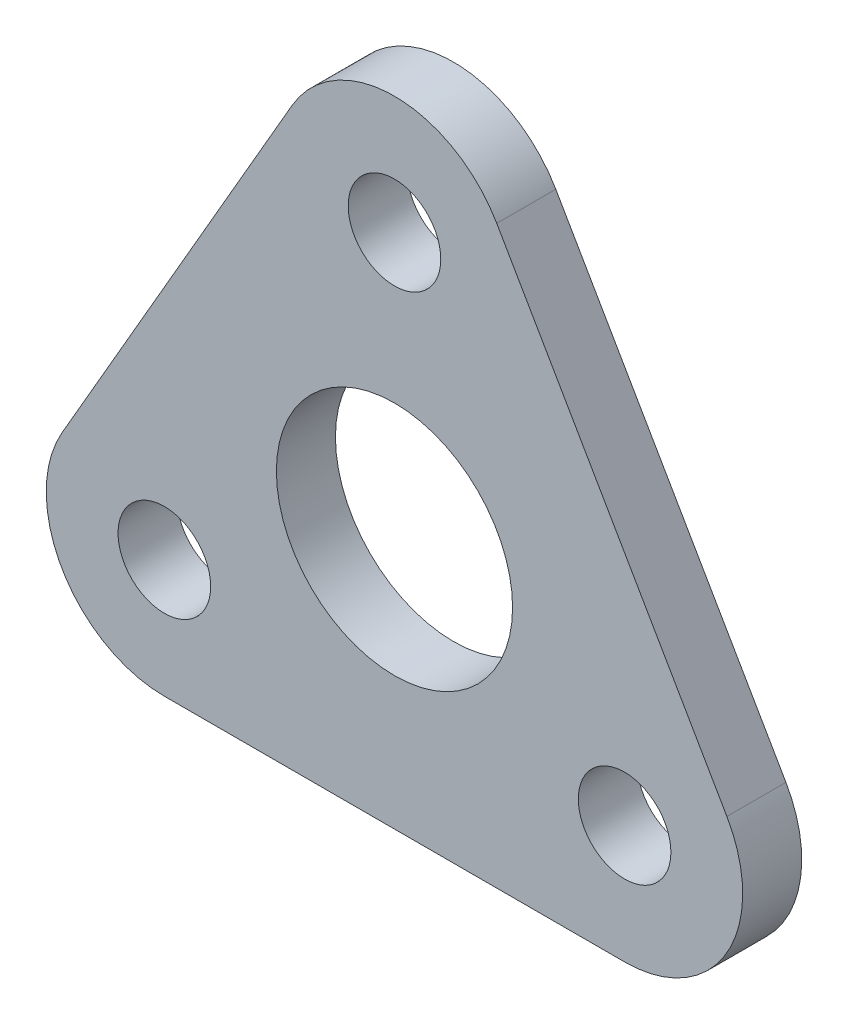
SolidWorks part; units mm, degrees
material "6061-T6 (SS)"
ref_plane "Front Plane" through (0, 0, 0) normal (0, 0, 1) x (1, 0, 0)
ref_plane "Top Plane" through (0, 0, 0) normal (0, 1, 0) x (1, 0, 0)
ref_plane "Right Plane" through (0, 0, 0) normal (1, 0, 0) x (0, 0, -1)
sketch "Sketch1" plane through (0, 0, 0) normal (0, 0, 1) x (1, 0, 0)
  line L3 (0, 14.2875) -> (12.3733, -7.1438) construction
  line L4 (12.3733, -7.1438) -> (-12.3733, -7.1438) construction
  line L5 (-12.3733, -7.1438) -> (0, 14.2875) construction
  line L6 (0, 26.9875) -> (23.3719, -13.4938)
  line L7 (23.3719, -13.4938) -> (-23.3719, -13.4938)
  line L8 (-23.3719, -13.4938) -> (0, 26.9875)
  circle A0 centre (0, 0) radius 6.35
  circle A1 centre (0, 14.2875) radius 2.4892
  circle A2 centre (12.3733, -7.1438) radius 2.4892
  circle A3 centre (-12.3733, -7.1438) radius 2.4892
  point P11 (0, 0)
  dimension "D1" = 12.7
  dimension "D2" = 4.9784
  dimension "D3" = 14.2875
  dimension "D5" = 6.35
  dimension "D4" = 3
extrude "Boss-Extrude1" add sketch "Sketch1" along normal blind 3.175
fillet "Fillet1" radius 6.35 3 edges at (23.3719, -13.4938, 1.5875) (-23.3719, -13.4938, 1.5875) (0, 26.9875, 1.5875)
